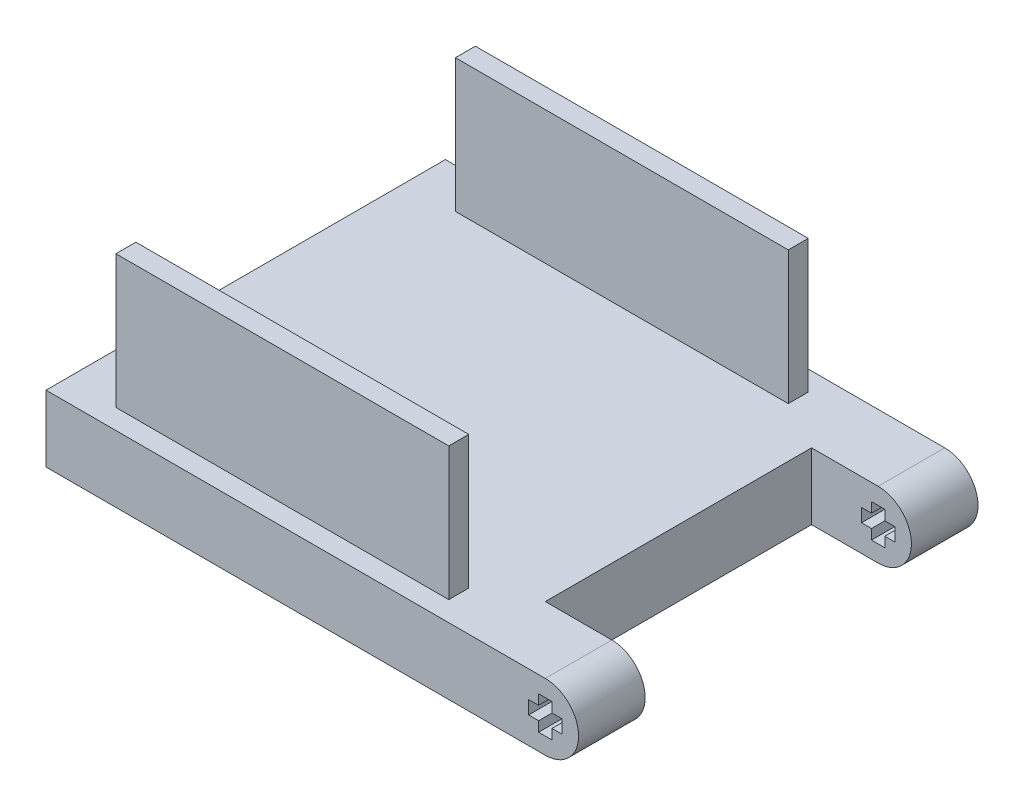
SolidWorks part; units mm, degrees
ref_plane "Front Plane" through (0, 0, 0) normal (0, 0, 1) x (1, 0, 0)
ref_plane "Top Plane" through (0, 0, 0) normal (0, 1, 0) x (1, 0, 0)
ref_plane "Right Plane" through (0, 0, 0) normal (1, 0, 0) x (0, 0, -1)
sketch "Sketch1" plane through (0, 0, 0) normal (0, 1, 0) x (1, 0, 0)
  line L8 (0, 0) -> (0, 60)
  line L9 (0, 60) -> (65, 60)
  line L10 (65, 60) -> (65, 0)
  line L11 (65, 0) -> (0, 0)
  dimension "D1" = 65
  dimension "D2" = 60
extrude "Boss-Extrude1" add sketch "Sketch1" along normal blind 10
sketch "Sketch2" plane through (0, 0, -60) normal (0, 0, -1) x (-1, 0, 0)
  line L0 (-65, 10) -> (-75, 10)
  line L1 (-65, 0) -> (-75, 0)
  line L2 (-75, 10) -> (-75, 0) construction
  line L3 (-65, 10) -> (-65, 0)
  arc A0 (-75, 10) -> (-75, 0) centre (-75, 5) ccw
  dimension "D1" = 10
extrude "Boss-Extrude2" add sketch "Sketch2" against normal blind 10
sketch "Sketch6" plane through (0, 0, 0) normal (0, 0, 1) x (1, 0, 0)
  line L0 (65, 10) -> (75, 10)
  line L1 (65, 0) -> (75, 0)
  line L2 (75, 10) -> (75, 0) construction
  line L3 (65, 10) -> (65, 0)
  arc A0 (75, 0) -> (75, 10) centre (75, 5) ccw
  dimension "D1" = 10
extrude "Boss-Extrude3" add sketch "Sketch6" against normal blind 10
sketch "Sketch7" plane through (0, 0, 0) normal (0, 0, 1) x (1, 0, 0)
  line L0 (75, 10) -> (75, 0) construction
  line L9 (74, 7.5) -> (76, 7.5)
  line L10 (74, 7.5) -> (74, 2.5)
  line L11 (74, 2.5) -> (76, 2.5)
  line L12 (76, 7.5) -> (76, 2.5)
  line L13 (74, 7.5) -> (76, 2.5) construction
  line L14 (74, 2.5) -> (76, 7.5) construction
  line L15 (72.5, 6) -> (77.5, 6)
  line L16 (72.5, 6) -> (72.5, 4)
  line L17 (72.5, 4) -> (77.5, 4)
  line L18 (77.5, 6) -> (77.5, 4)
  line L19 (72.5, 6) -> (77.5, 4) construction
  line L20 (72.5, 4) -> (77.5, 6) construction
  point P0 (75, 5)
  point P1 (75, 5)
  point P2 (75, 5)
  dimension "D2" = 2
  dimension "D3" = 2
  dimension "D4" = 5
  dimension "D5" = 5
extrude "Cut-Extrude1" cut sketch "Sketch7" against normal through all and the other way through all contours L18 L15 L12 L17 | L10 L15 L12 L9 | L10 L17 L12 L15 | L16 L17 L10 L15 | L17 L10 L11 L12
sketch "Sketch8" plane through (0, 10, 0) normal (0, 1, 0) x (1, 0, 0)
  line L0 (7.5, 3) -> (7.5, 6)
  line L1 (7.5, 6) -> (57.5, 6)
  line L2 (57.5, 6) -> (57.5, 3)
  line L3 (57.5, 3) -> (7.5, 3)
  line L4 (7.5, 54) -> (7.5, 57)
  line L5 (7.5, 57) -> (57.5, 57)
  line L6 (57.5, 57) -> (57.5, 54)
  line L7 (57.5, 54) -> (7.5, 54)
  line L8 (0, 30) -> (65, 30) construction
  line L9 (0, 60) -> (0, 0) construction
  line L10 (65, 10) -> (65, 50) construction
  line L11 (32.5, 6) -> (32.5, 54) construction
  point P16 (32.5, 30)
  point P17 (32.5, 30)
  dimension "D1" = 3
  dimension "D2" = 3
  dimension "D3" = 48
  dimension "D4" = 50
extrude "Boss-Extrude4" add sketch "Sketch8" along normal blind 20
